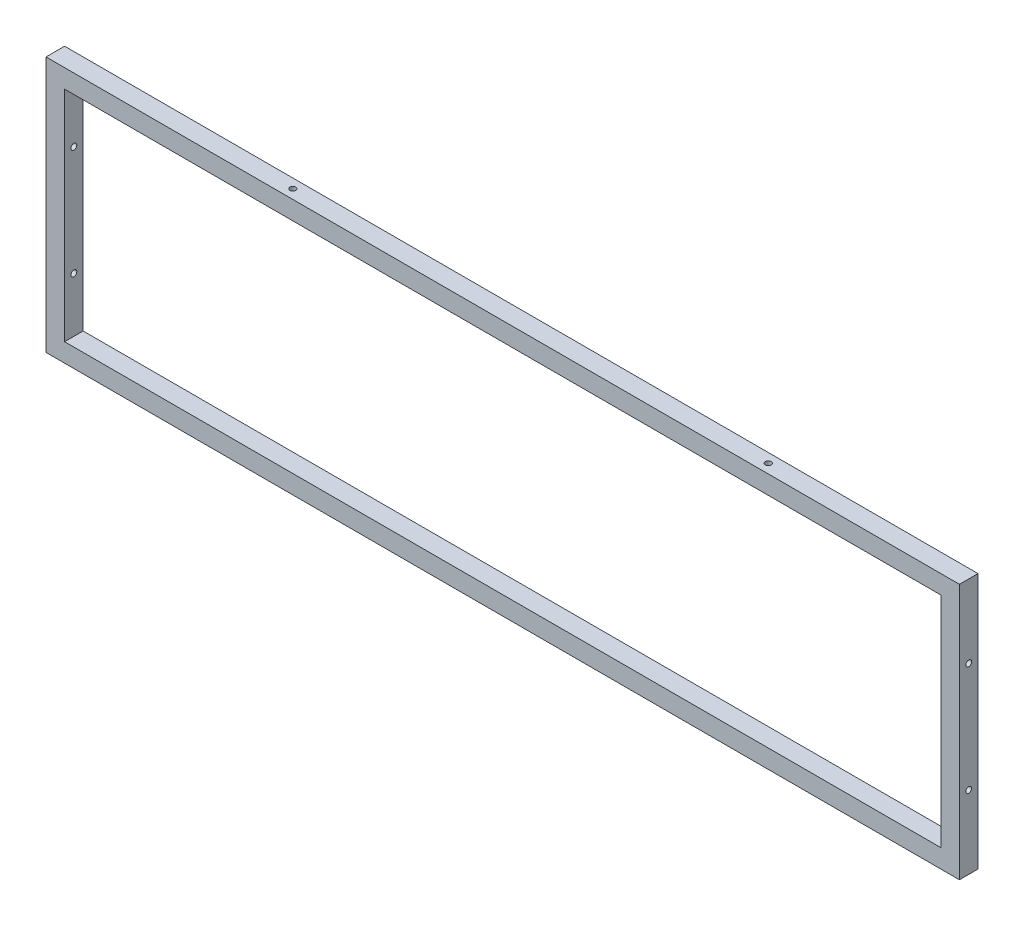
SolidWorks part; units mm, degrees
ref_plane "Front Plane" through (0, 0, 0) normal (0, 0, 1) x (1, 0, 0)
ref_plane "Top Plane" through (0, 0, 0) normal (0, 1, 0) x (1, 0, 0)
ref_plane "Right Plane" through (0, 0, 0) normal (1, 0, 0) x (0, 0, -1)
sketch "Sketch1" plane through (0, 0, 0) normal (0, 0, 1) x (1, 0, 0)
  line L0 (0, 0) -> (1249.2, 0)
  line L1 (0, 0) -> (0, -350)
  line L2 (1249.2, 0) -> (1249.2, -350)
  line L3 (0, -350) -> (1249.2, -350)
  line L4 (0, -267.0255) -> (25.4, -267.0255) construction
  line L5 (25.4, -324.6) -> (25.4, -25.4)
  line L6 (687.5822, 0) -> (687.5822, -25.4) construction
  line L7 (1249.2, -139.9048) -> (1223.8, -139.9048) construction
  line L8 (853.3219, -350) -> (853.3219, -324.6) construction
  line L9 (1223.8, -25.4) -> (1223.8, -324.6)
  line L10 (1223.8, -25.4) -> (25.4, -25.4)
  line L11 (1223.8, -324.6) -> (25.4, -324.6)
  dimension "D1" = 1249.2
  dimension "D2" = 350
  dimension "D3" = 25.4
  dimension "D4" = 25.4
  dimension "D5" = 25.4
  dimension "D6" = 25.4
extrude "Boss-Extrude1" add sketch "Sketch1" against normal blind 25.4
sketch "Sketch2" plane through (0, 0, 0) normal (0, 1, 0) x (1, 0, 0)
  line L0 (0, 12.7) -> (1249.2, 12.7) construction
  line L1 (0, 25.4) -> (0, 0) construction
  line L2 (1249.2, 25.4) -> (1249.2, 0) construction
  line L3 (0, 71.998) -> (1300.0541, 71.998) construction
  line L4 (0, 71.998) -> (0, 185.3231) construction
  line L5 (0, 185.3231) -> (325, 185.3231) construction
  line L6 (1300.0541, 116.801) -> (975.0541, 116.801) construction
  line L7 (1249.2, 25.4) -> (0, 25.4) construction
  circle A0 centre (325, 12.7) radius 4
  circle A1 centre (975.0541, 12.7) radius 4
  dimension "D2" = 325
  dimension "D1" = 325
extrude "Cut-Extrude3" cut sketch "Sketch2" against normal blind 25.4 contours A0 | A1
sketch "Sketch3" plane through (0, 0, 0) normal (1, 0, 0) x (0, 0, -1)
  line L0 (0, -350) -> (-98.407, -350) construction
  line L1 (0, 0) -> (-44.6296, 0) construction
  line L2 (-44.6296, 0) -> (-44.6296, -350) construction
  line L3 (-22.3148, 0) -> (-22.3148, -100) construction
  line L4 (-22.3148, -350) -> (-22.3148, -250) construction
  line L5 (12.7, 0) -> (12.7, -350) construction
  line L6 (25.4, 0) -> (0, 0) construction
  line L7 (25.4, -350) -> (0, -350) construction
  circle A0 centre (12.7, -100) radius 4
  circle A1 centre (12.7, -250) radius 4
  dimension "D4" = 150
  dimension "D1" = 350
  dimension "D2" = 100
  dimension "D3" = 100
extrude "Cut-Extrude10" cut sketch "Sketch3" along normal blind 5341.4
